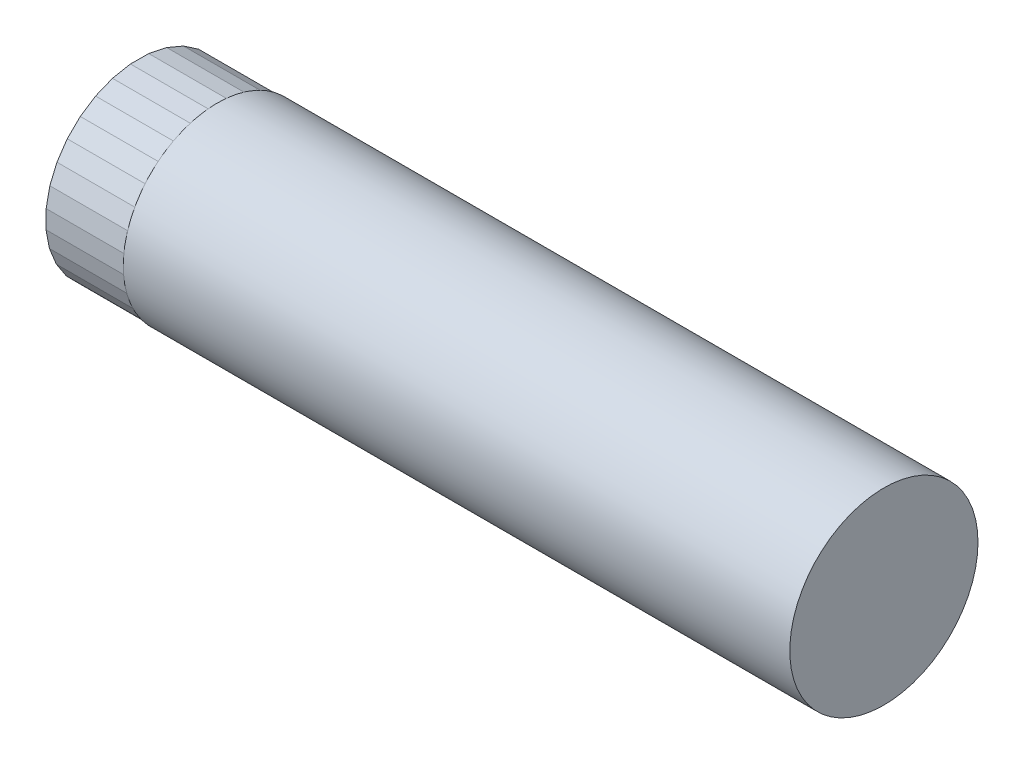
SolidWorks part; units mm, degrees
ref_plane "前视基准面" through (0, 0, 0) normal (0, 0, 1) x (1, 0, 0)
ref_plane "上视基准面" through (0, 0, 0) normal (0, 1, 0) x (1, 0, 0)
ref_plane "右视基准面" through (0, 0, 0) normal (1, 0, 0) x (0, 0, -1)
other "Configuration Table"
sketch "草图1" plane through (0, 0, 0) normal (1, 0, 0) x (0, 0, -1)
  circle A0 centre (0, 0) radius 6
  dimension "D1" = 12
extrude "凸台-拉伸1" add sketch "草图1" along normal blind 42.5
sketch "草图2" plane through (0, 0, 0) normal (-1, 0, 0) x (0, 0, 1)
  line L0 (-5.9224, 0.5378) -> (-5.9136, -0.6279)
  line L1 (4.6255, -3.7375) -> (5.2658, -2.7633)
  line L2 (5.2658, -2.7633) -> (5.7037, -1.6829)
  line L3 (5.7037, -1.6829) -> (5.9224, -0.5378)
  line L4 (5.9224, -0.5378) -> (5.9136, 0.6279)
  line L5 (5.9136, 0.6279) -> (5.6774, 1.7695)
  line L6 (5.6774, 1.7695) -> (5.2231, 2.8431)
  line L7 (5.2231, 2.8431) -> (4.5681, 3.8075)
  line L8 (4.5681, 3.8075) -> (3.7375, 4.6255)
  line L9 (3.7375, 4.6255) -> (2.7633, 5.2658)
  line L10 (2.7633, 5.2658) -> (1.6829, 5.7037)
  line L11 (1.6829, 5.7037) -> (0.5378, 5.9224)
  line L12 (0.5378, 5.9224) -> (-0.6279, 5.9136)
  line L13 (-0.6279, 5.9136) -> (-1.7695, 5.6774)
  line L14 (-1.7695, 5.6774) -> (-2.8431, 5.2231)
  line L15 (-2.8431, 5.2231) -> (-3.8075, 4.5681)
  line L16 (-3.8075, 4.5681) -> (-4.6255, 3.7375)
  line L17 (-4.6255, 3.7375) -> (-5.2658, 2.7633)
  line L18 (-5.2658, 2.7633) -> (-5.7037, 1.6829)
  line L19 (-5.7037, 1.6829) -> (-5.9224, 0.5378)
  line L20 (-5.9136, -0.6279) -> (-5.6774, -1.7695)
  line L21 (-5.6774, -1.7695) -> (-5.2231, -2.8431)
  line L22 (-5.2231, -2.8431) -> (-4.5681, -3.8075)
  line L23 (-4.5681, -3.8075) -> (-3.7375, -4.6255)
  line L24 (-3.7375, -4.6255) -> (-2.7633, -5.2658)
  line L25 (-2.7633, -5.2658) -> (-1.6829, -5.7037)
  line L26 (-1.6829, -5.7037) -> (-0.5378, -5.9224)
  line L27 (-0.5378, -5.9224) -> (0.6279, -5.9136)
  line L28 (0.6279, -5.9136) -> (1.7695, -5.6774)
  line L29 (1.7695, -5.6774) -> (2.8431, -5.2231)
  line L30 (2.8431, -5.2231) -> (3.8075, -4.5681)
  line L31 (3.8075, -4.5681) -> (4.6255, -3.7375)
  circle A0 centre (0, 0) radius 5.9468 construction
extrude "凸台-拉伸2" add sketch "草图2" along normal blind 5
